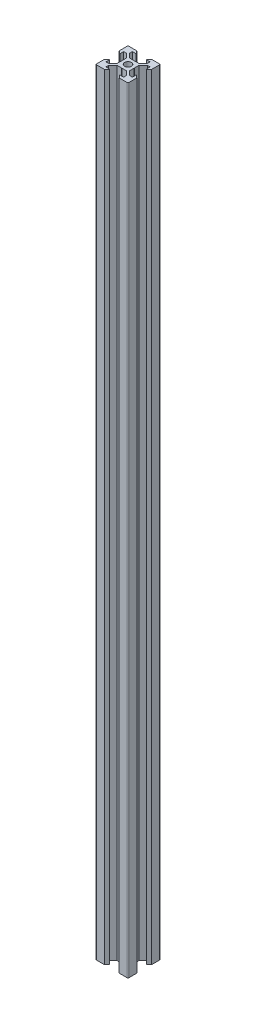
SolidWorks part; units mm, degrees
ref_plane "Front Plane" through (0, 0, 0) normal (0, 0, 1) x (1, 0, 0)
ref_plane "Top Plane" through (0, 0, 0) normal (0, 1, 0) x (1, 0, 0)
ref_plane "Right Plane" through (0, 0, 0) normal (1, 0, 0) x (0, 0, -1)
sketch "Sketch1" plane through (0, 0, 0) normal (0, 1, 0) x (1, 0, 0)
  line L0 (0, 20) -> (20, 0) construction
  line L1 (20, 5.42) -> (20, 0.5)
  line L2 (18.4507, 6.875) -> (20, 5.42)
  line L3 (18.2007, 6.875) -> (18.4507, 6.875)
  line L4 (18.2007, 6.875) -> (18.2007, 4.5)
  line L5 (20, 20) -> (0, 0) construction
  line L6 (15.5, 16.5607) -> (12.84, 13.9007)
  line L7 (16.5607, 15.5) -> (13.9007, 12.84)
  line L8 (10, 10) -> (20, 10) construction
  line L9 (10, 10) -> (10, 20) construction
  line L10 (13.9007, 10.25) -> (13.9007, 12.84)
  line L11 (10.25, 13.9007) -> (12.84, 13.9007)
  line L12 (10, 13.6507) -> (10.25, 13.9007)
  line L13 (13.9007, 10.25) -> (13.6507, 10)
  line L14 (13.125, 18.2007) -> (15.5, 18.2007)
  line L15 (18.2007, 15.5) -> (18.2007, 13.13)
  line L16 (13.125, 18.2007) -> (13.125, 18.4507)
  line L17 (18.2007, 13.13) -> (18.4507, 13.13)
  line L18 (13.125, 18.4507) -> (14.58, 20)
  line L19 (18.4507, 13.13) -> (20, 14.58)
  line L20 (14.58, 20) -> (19.5, 20)
  line L21 (20, 14.58) -> (20, 19.5)
  line L22 (15.5, 18.2007) -> (15.5, 16.5607)
  line L23 (16.5607, 15.5) -> (18.2007, 15.5)
  line L24 (18.2007, 4.5) -> (16.5607, 4.5)
  line L25 (16.5607, 4.5) -> (13.9007, 7.16)
  line L26 (13.9007, 9.75) -> (13.9007, 7.16)
  line L27 (13.6507, 10) -> (13.9007, 9.75)
  line L28 (10.25, 6.0993) -> (10, 6.3493)
  line L29 (10.25, 6.0993) -> (12.84, 6.0993)
  line L30 (15.5, 3.4393) -> (12.84, 6.0993)
  line L31 (15.5, 3.4393) -> (15.5, 1.7993)
  line L32 (15.5, 1.7993) -> (13.13, 1.7993)
  line L33 (13.13, 1.7993) -> (13.13, 1.5493)
  line L34 (13.13, 1.5493) -> (14.58, 0)
  line L35 (14.58, 0) -> (19.5, 0)
  line L36 (5.42, 0) -> (0.5, 0)
  line L37 (6.875, 1.5493) -> (5.42, 0)
  line L38 (6.875, 1.7993) -> (6.875, 1.5493)
  line L39 (6.875, 1.7993) -> (4.5, 1.7993)
  line L40 (4.5, 1.7993) -> (4.5, 3.4393)
  line L41 (4.5, 3.4393) -> (7.16, 6.0993)
  line L42 (9.75, 6.0993) -> (7.16, 6.0993)
  line L43 (10, 6.3493) -> (9.75, 6.0993)
  line L44 (6.0993, 9.75) -> (6.3493, 10)
  line L45 (6.0993, 9.75) -> (6.0993, 7.16)
  line L46 (3.4393, 4.5) -> (6.0993, 7.16)
  line L47 (3.4393, 4.5) -> (1.7993, 4.5)
  line L48 (1.7993, 4.5) -> (1.7993, 6.87)
  line L49 (1.7993, 6.87) -> (1.5493, 6.87)
  line L50 (1.5493, 6.87) -> (0, 5.42)
  line L51 (0, 5.42) -> (0, 0.5)
  line L52 (0, 14.58) -> (0, 19.5)
  line L53 (1.5493, 13.125) -> (0, 14.58)
  line L54 (1.7993, 13.125) -> (1.5493, 13.125)
  line L55 (1.7993, 13.125) -> (1.7993, 15.5)
  line L56 (1.7993, 15.5) -> (3.4393, 15.5)
  line L57 (3.4393, 15.5) -> (6.0993, 12.84)
  line L58 (6.0993, 10.25) -> (6.0993, 12.84)
  line L59 (6.3493, 10) -> (6.0993, 10.25)
  line L60 (9.75, 13.9007) -> (10, 13.6507)
  line L61 (9.75, 13.9007) -> (7.16, 13.9007)
  line L62 (4.5, 16.5607) -> (7.16, 13.9007)
  line L63 (4.5, 16.5607) -> (4.5, 18.2007)
  line L64 (4.5, 18.2007) -> (6.87, 18.2007)
  line L65 (6.87, 18.2007) -> (6.87, 18.4507)
  line L66 (6.87, 18.4507) -> (5.42, 20)
  line L67 (5.42, 20) -> (0.5, 20)
  arc A0 (12.1, 10) -> (10, 12.1) centre (10, 10) ccw
  arc A1 (19.5, 20) -> (20, 19.5) centre (19.5, 19.5) cw
  arc A2 (10, 7.9) -> (12.1, 10) centre (10, 10) ccw
  arc A3 (20, 0.5) -> (19.5, 0) centre (19.5, 0.5) cw
  arc A4 (7.9, 10) -> (10, 7.9) centre (10, 10) ccw
  arc A5 (0.5, 0) -> (0, 0.5) centre (0.5, 0.5) cw
  arc A6 (10, 12.1) -> (7.9, 10) centre (10, 10) ccw
  arc A7 (0, 19.5) -> (0.5, 20) centre (0.5, 19.5) cw
  point P95 (10, 10)
  dimension "D3" = 1.5
  dimension "D4" = 4.2
  dimension "D20" = 0.5
  dimension "D1" = 20
  dimension "D2" = 20
  dimension "D5" = 4
  dimension "D7" = 0.25
  dimension "D8" = 0.25
  dimension "D9" = 4.3
  dimension "D10" = 4.3
  dimension "D11" = 3.125
  dimension "D12" = 3.13
  dimension "D13" = 4.58
  dimension "D14" = 0.25
  dimension "D15" = 4.58
  dimension "D16" = 0.25
  dimension "D17" = 5.5
  dimension "D18" = 5.5
  dimension "D19" = 0.25
extrude "Boss-Extrude1" add sketch "Sketch1" along normal blind 480
